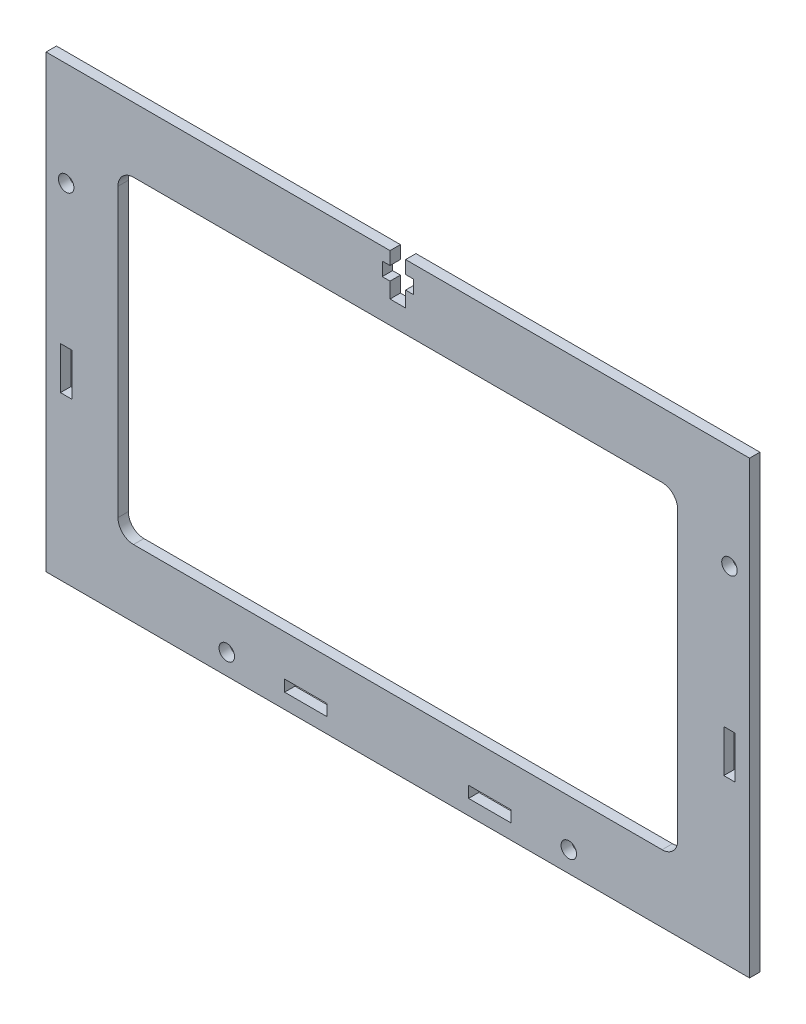
SolidWorks part; units mm, degrees
ref_plane "前视基准面" through (0, 0, 0) normal (0, 0, 1) x (1, 0, 0)
ref_plane "上视基准面" through (0, 0, 0) normal (0, 1, 0) x (1, 0, 0)
ref_plane "右视基准面" through (0, 0, 0) normal (1, 0, 0) x (0, 0, -1)
sketch "草图1" plane through (0, 0, 0) normal (0, 0, 1) x (1, 0, 0)
  line L0 (21.5651, -10.096) -> (13.5651, -8.096) construction
  line L1 (32.8151, -9.096) -> (-33.1849, -9.096) construction
  line L3 (-34.6849, -10.096) -> (-31.6849, -8.096) construction
  line L4 (-21.9349, -10.096) -> (-13.9349, -8.096) construction
  line L5 (-22.0349, -10.196) -> (-13.8349, -10.196)
  line L6 (-13.8349, -7.996) -> (-13.8349, -10.196)
  line L7 (-22.0349, -7.996) -> (-13.8349, -7.996)
  line L8 (-22.0349, -7.996) -> (-22.0349, -10.196)
  line L12 (-52.1849, -13.096) -> (-18.9349, -13.096)
  line L13 (64.9151, 18.2415) -> (62.7151, 18.2415)
  line L15 (34.3151, -10.096) -> (31.3151, -8.096) construction
  line L16 (21.6651, -7.996) -> (21.6651, -10.196)
  line L17 (21.6651, -7.996) -> (13.4651, -7.996)
  line L18 (13.4651, -7.996) -> (13.4651, -10.196)
  line L19 (67.6951, -13.096) -> (18.5651, -13.096)
  line L20 (64.9151, 18.2415) -> (64.9151, 26.4415)
  line L21 (-18.9349, -13.096) -> (18.5651, -13.096)
  line L22 (64.9151, 26.4415) -> (62.7151, 26.4415)
  line L25 (-63.0849, 18.2415) -> (-63.0849, 26.4415)
  line L26 (-65.2849, 26.4415) -> (-63.0849, 26.4415)
  line L27 (-65.2849, 18.2415) -> (-65.2849, 26.4415)
  line L28 (-65.2849, 18.2415) -> (-63.0849, 18.2415)
  line L29 (21.6651, -10.196) -> (13.4651, -10.196)
  line L34 (62.7151, 18.2415) -> (62.7151, 26.4415)
  line L35 (-52.1849, -13.096) -> (-68.0618, -13.096)
  line L41 (-49.1849, 53.779) -> (-49.1849, 33.779) construction
  line L42 (-49.1849, 53.779) -> (-49.1849, 73.779) construction
  line L43 (-68.0618, -13.096) -> (-68.0618, 73.779)
  line L46 (67.6951, -13.096) -> (67.6951, 73.779)
  line L47 (54.8151, 73.779) -> (54.8151, 87.1175) construction
  line L48 (54.8151, 87.1175) -> (171.8151, 87.1175) construction
  line L49 (-49.1849, 33.779) -> (206.8345, 33.779) construction
  line L50 (67.6951, 73.779) -> (1.3151, 73.779)
  line L51 (54.8151, 87.1175) -> (-62.1849, 87.1175) construction
  line L52 (-0.1849, -9.096) -> (-0.1849, 138.1567) construction
  line L53 (-1.6849, 71.279) -> (-3.1849, 71.279)
  line L61 (1.3151, 71.279) -> (2.8151, 71.279)
  line L62 (1.3151, 73.779) -> (1.3151, 71.279)
  line L63 (-3.1849, 71.279) -> (-3.1849, 68.679)
  line L64 (-3.1849, 68.679) -> (-1.6849, 68.679)
  line L65 (-1.6849, 68.679) -> (-1.6849, 65.679)
  line L66 (1.3151, 65.679) -> (-1.6849, 65.679)
  line L67 (1.3151, 68.679) -> (1.3151, 65.679)
  line L68 (2.8151, 68.679) -> (1.3151, 68.679)
  line L69 (2.8151, 71.279) -> (2.8151, 68.679)
  line L70 (-1.6849, 71.279) -> (-1.6849, 73.779)
  line L71 (-68.0618, 73.779) -> (-1.6849, 73.779)
  line L73 (-0.1849, 73.779) -> (-0.1849, 71.279) construction
  line L104 (-0.1849, 22.3415) -> (67.6951, 22.3415) construction
  line L105 (53.8151, 58.279) -> (53.8151, 2.904)
  line L106 (63.8151, 71.279) -> (-64.1849, 71.279) construction
  line L107 (63.8151, 71.279) -> (63.8151, -10.096) construction
  line L108 (63.8151, -10.096) -> (-64.1849, -10.096) construction
  line L109 (-64.1849, 71.279) -> (-64.1849, -10.096) construction
  line L110 (50.8151, -0.096) -> (-51.1849, -0.096)
  line L111 (-54.1849, 58.279) -> (-54.1849, 2.904)
  line L112 (50.8151, 61.279) -> (-51.1849, 61.279)
  line L113 (53.8151, -0.096) -> (-54.1849, -0.096) construction
  line L114 (53.8151, 61.279) -> (53.8151, -0.096) construction
  line L115 (-54.1849, 61.279) -> (-54.1849, -0.096) construction
  line L116 (53.8151, 61.279) -> (-54.1849, 61.279) construction
  line L117 (101.8151, 53.779) -> (63.8151, 53.779) construction
  circle A0 centre (-33.1849, -9.096) radius 1.5
  circle A2 centre (32.8151, -9.096) radius 1.5
  arc A12 (50.8151, -0.096) -> (53.8151, 2.904) centre (50.8151, 2.904) ccw
  arc A13 (-51.1849, -0.096) -> (-54.1849, 2.904) centre (-51.1849, 2.904) cw
  arc A14 (-54.1849, 58.279) -> (-51.1849, 61.279) centre (-51.1849, 58.279) cw
  arc A15 (50.8151, 61.279) -> (53.8151, 58.279) centre (50.8151, 58.279) cw
  circle A16 centre (-64.1849, 53.779) radius 1.5
  circle A17 centre (63.8151, 53.779) radius 1.5
  point P66 (-19.749, 73.5671)
  dimension "D1" = 10
  dimension "D2" = 3
  dimension "D4" = 3
extrude "凸台-拉伸1" add sketch "草图1" along normal blind 2 contours L12 L21 L19
